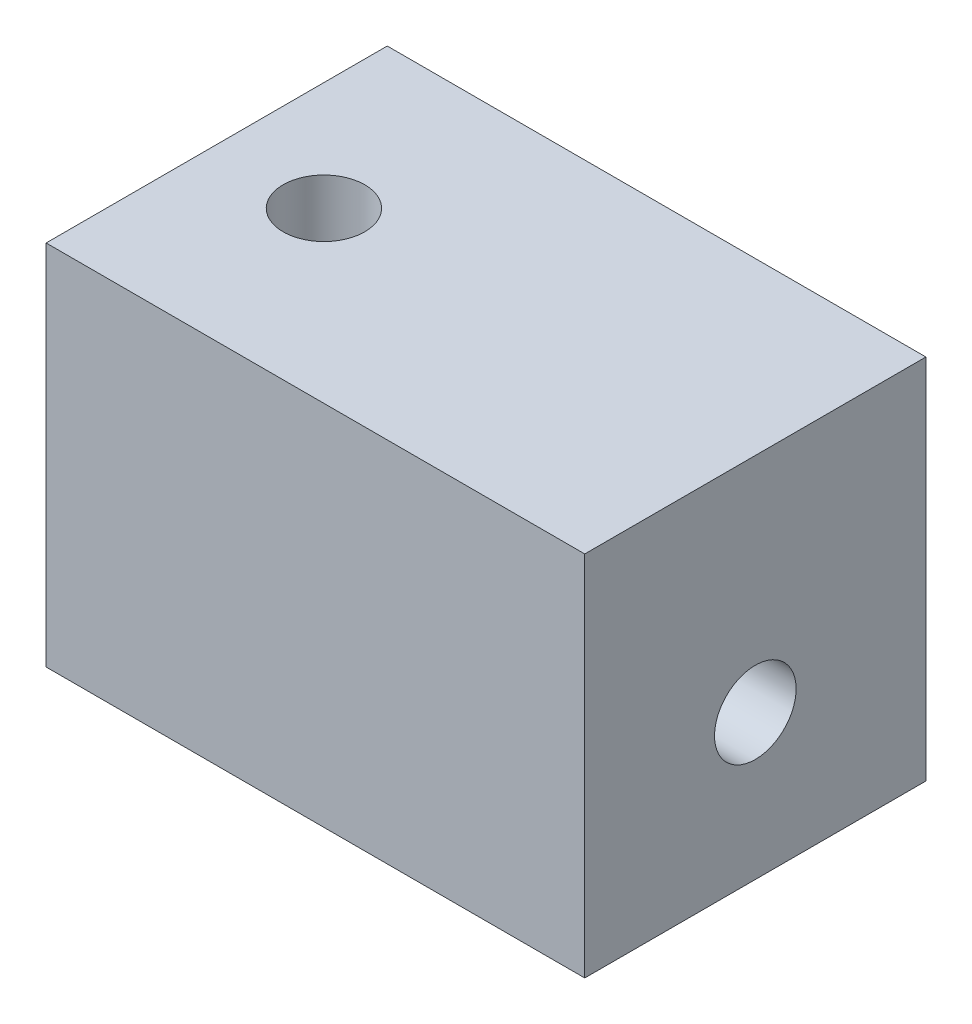
SolidWorks part; units mm, degrees
other "标注1"
sketch "草图14" plane through (-27, 5, 0) normal (-0.8193, 0.3071, -0.4842) x (-0.4621, 0.1462, 0.8747)
other "标注2"
sketch "草图21" plane through (-27, -16.5, -4) normal (-0.177, -0.9623, -0.2067) x (-0.9756, 0.1993, -0.0925)
material "ABS"
ref_plane "Front Plane" through (0, 0, 0) normal (0, 0, 1) x (1, 0, 0)
ref_plane "Top Plane" through (0, 0, 0) normal (0, 1, 0) x (1, 0, 0)
ref_plane "Right Plane" through (0, 0, 0) normal (1, 0, 0) x (0, 0, -1)
sketch "Sketch1" plane through (0, 0, 0) normal (0, 0, 1) x (1, 0, 0)
  line L0 (-30, 0) -> (-30, 6)
  line L1 (0, 0) -> (-30, 0)
  line L2 (0, 0) -> (0, -18)
  line L3 (0, -18) -> (-30, -18) construction
  line L4 (-30, 0) -> (-30, -18) construction
  line L5 (-30, 6) -> (6, 6)
  line L6 (6, 6) -> (6, -18)
  line L7 (6, -18) -> (0, -18)
  dimension "D1" = 30
  dimension "D2" = 18
  dimension "D3" = 6
  dimension "D4" = 6
extrude "Boss-Extrude1" add sketch "Sketch1" along normal blind 12.9
sketch "Sketch2" plane through (0, 0, 0) normal (0, -1, 0) x (1, 0, 0)
  line L0 (-30, 6.55) -> (0, 6.55) construction
  line L2 (0, 12.9) -> (0, 0) construction
  line L3 (6, 12.9) -> (-30, 12.9) construction
  circle A0 centre (-20.33, 6.55) radius 2.5
  dimension "D1" = 5
  dimension "D2" = 20.33
  dimension "D3" = 6.35
extrude "Cut-Extrude1" cut sketch "Sketch2" against normal through all
sketch "Sketch3" plane through (0, 0, 0) normal (-1, 0, 0) x (0, 0, 1)
  line L0 (6.45, -18) -> (6.45, 0) construction
  line L1 (12.9, -18) -> (0, -18) construction
  line L2 (12.9, 0) -> (0, 0) construction
  circle A0 centre (6.45, -7.63) radius 2.5
  dimension "D1" = 5
  dimension "D2" = 7.63
extrude "Cut-Extrude2" cut sketch "Sketch3" against normal through all
sketch "Sketch5" plane through (0, 0, 12.9) normal (0, 0, 1) x (1, 0, 0)
  line L0 (-30, 6) -> (-30, 0) construction
  line L1 (6, 6) -> (-30, 6)
  line L2 (6, 6) -> (6, -18)
  line L3 (6, -18) -> (-30, -18)
  line L4 (-30, 6) -> (-30, -18)
  line L5 (0, -18) -> (6, -18) construction
extrude "Boss-Extrude3" add sketch "Sketch5" along normal blind 4
sketch "Sketch6" plane through (0, 0, 12.9) normal (0, 0, -1) x (-1, 0, 0)
  line L0 (30, 0) -> (0, 0) construction
  line L1 (30, -18) -> (12.7, -18)
  line L2 (30, -18) -> (30, -12.7)
  line L3 (30, -12.7) -> (12.7, -12.7)
  line L4 (12.7, -18) -> (12.7, -12.7)
  line L5 (0, 0) -> (0, -18) construction
  dimension "D1" = 12.7
  dimension "D2" = 12.7
extrude "Boss-Extrude4" add sketch "Sketch6" along normal blind 12.9
sketch "Sketch7" plane through (0, -12.7, 0) normal (0, 1, 0) x (1, 0, 0)
  line L0 (-30, -6.45) -> (-12.7, -6.45) construction
  line L1 (-30, 0) -> (-30, -12.9) construction
  line L2 (-12.7, 0) -> (-12.7, -12.9) construction
  line L3 (-12.7, 0) -> (-12.7, -12.9) construction
  circle A0 centre (-20.33, -6.45) radius 2.5
  dimension "D1" = 5
  dimension "D2" = 7.63
extrude "Cut-Extrude3" cut sketch "Sketch7" against normal through all
sketch "草图4" plane through (0, 0, 0) normal (0, 0, -1) x (-1, 0, 0)
  line L0 (30, 6) -> (9, 6)
  line L1 (-6, 6) -> (30, 6) construction
  line L2 (9, 6) -> (9, -4)
  line L3 (9, -4) -> (11, -4)
  line L4 (11, -4) -> (11, -18)
  line L5 (12.7, -18) -> (0, -18) construction
  line L6 (11, -18) -> (30, -18)
  line L7 (30, -18) -> (30, 6)
  dimension "D1" = 19
  dimension "D2" = 21
  dimension "D3" = 10
extrude "凸台-拉伸3" add sketch "草图4" along normal blind 4
sketch "草图5" plane through (0, -18, 0) normal (0, -1, 0) x (1, 0, 0)
  line L9 (-30, -4) -> (-27, -4)
  line L10 (-30, -4) -> (-30, 16.9)
  line L11 (-30, 16.9) -> (-27, 16.9)
  line L12 (-27, -4) -> (-27, 16.9)
  dimension "D1" = 3
  dimension "D2" = 20.9
extrude "切除-拉伸1" cut sketch "草图5" against normal through all
sketch "草图6" plane through (0, 0, -4) normal (0, 0, -1) x (-1, 0, 0)
  line L0 (11, -18) -> (11, -14)
  line L1 (11, -4) -> (11, -18) construction
  line L2 (11, -14) -> (13.1, -18)
  line L3 (11, -18) -> (27, -18) construction
  line L4 (13.1, -18) -> (11, -18)
  dimension "D1" = 2.1
  dimension "D2" = 4
extrude "切除-拉伸2" cut sketch "草图6" against normal blind 4
sketch "草图7" plane through (6, 0, 0) normal (1, 0, 0) x (0, 0, -1)
  line L1 (-16.9, -18) -> (0, -18)
  line L2 (-16.9, -18) -> (-16.9, -16.5)
  line L3 (-16.9, -16.5) -> (0, -16.5)
  line L4 (0, -18) -> (0, -16.5)
  dimension "D1" = 1.5
  dimension "D2" = 16.9
extrude "切除-拉伸3" cut sketch "草图7" against normal blind 20
sketch "Sketch8" plane through (0, -16.5, 0) normal (0, -1, 0) x (1, 0, 0)
  line L0 (-13.1, 0) -> (-14, 0)
  line L1 (-14, 0) -> (-14, 12.9)
  line L2 (-14, 16.9) -> (-14, 0) construction
  line L3 (-14, 12.9) -> (-12.7, 12.9)
  line L5 (-27, 12.9) -> (0, 12.9) construction
  line L6 (-12.7, 12.9) -> (-12.7, 0)
  line L7 (-12.7, 0) -> (-14, 0)
extrude "Cut-Extrude5" cut sketch "Sketch8" against normal up to next
sketch "草图9" plane through (6, 0, 0) normal (1, 0, 0) x (0, 0, -1)
  line L1 (0, 6) -> (4, 6)
  line L2 (0, 6) -> (0, -18)
  line L3 (0, -18) -> (4, -18)
  line L4 (4, 6) -> (4, -18)
extrude "切除-拉伸4" cut sketch "草图9" against normal through all
sketch "草图11" plane through (-14, 0, 0) normal (1, 0, 0) x (0, 0, -1)
  line L1 (-16.9, -16.5) -> (0, -16.5)
  line L2 (-16.9, -16.5) -> (-16.9, -18)
  line L3 (-16.9, -18) -> (0, -18)
  line L4 (0, -16.5) -> (0, -18)
extrude "切除-拉伸6" cut sketch "草图11" against normal through all
sketch "草图13" plane through (-14, 0, 0) normal (1, 0, 0) x (0, 0, -1)
  line L1 (-12.9, -12.7) -> (0, -12.7)
  line L2 (-12.9, -12.7) -> (-12.9, -16.5)
  line L3 (-12.9, -16.5) -> (0, -16.5)
  line L4 (0, -12.7) -> (0, -16.5)
extrude "凸台-拉伸5" add sketch "草图13" along normal blind 1.3
sketch "草图17" plane through (0, 0, 0) normal (0, 0, -1) x (-1, 0, 0)
  line L0 (-6, 6) -> (-6, -16.5)
  line L1 (-6, -16.5) -> (0, -16.5)
  line L2 (0, -16.5) -> (0, -3.5)
  line L3 (0, 0) -> (0, -16.5) construction
  line L4 (0, -3.5) -> (12.7, -3.5)
  line L5 (12.7, -3.5) -> (12.7, 0)
  line L6 (27, 0) -> (0, 0) construction
  line L7 (12.7, 0) -> (16.2, 0)
  line L8 (16.2, 0) -> (16.2, -12.7)
  line L9 (27, -12.7) -> (12.7, -12.7) construction
  line L10 (16.2, -12.7) -> (12.7, -12.7)
  line L11 (12.7, -12.7) -> (12.7, -16.5)
  line L12 (12.7, -16.5) -> (0, -16.5)
  line L13 (12.7, -3.5) -> (12.7, -12.7)
  line L14 (-6, 6) -> (27, 6)
  line L15 (27, 6) -> (27, 0)
  line L16 (27, 0) -> (16.2, 0)
  line L17 (16.2, -12.7) -> (27, -12.7)
  line L18 (27, -12.7) -> (27, -16.5)
  line L19 (27, -16.5) -> (12.7, -16.5) construction
  line L20 (27, -16.5) -> (12.7, -16.5)
  dimension "D1" = 3.5
  dimension "D2" = 3.5
extrude "凸台-拉伸6" add sketch "草图17" along normal blind 4
sketch "草图19" plane through (0, -16.5, 0) normal (0, -1, 0) x (1, 0, 0)
  line L0 (-27, -4) -> (-12.7, -4) construction
  line L1 (-27, 16.9) -> (-16, 16.9)
  line L2 (-27, 16.9) -> (-27, -4)
  line L3 (-27, -4) -> (-16, -4)
  line L4 (-16, 16.9) -> (-16, -4)
  dimension "D1" = 11
